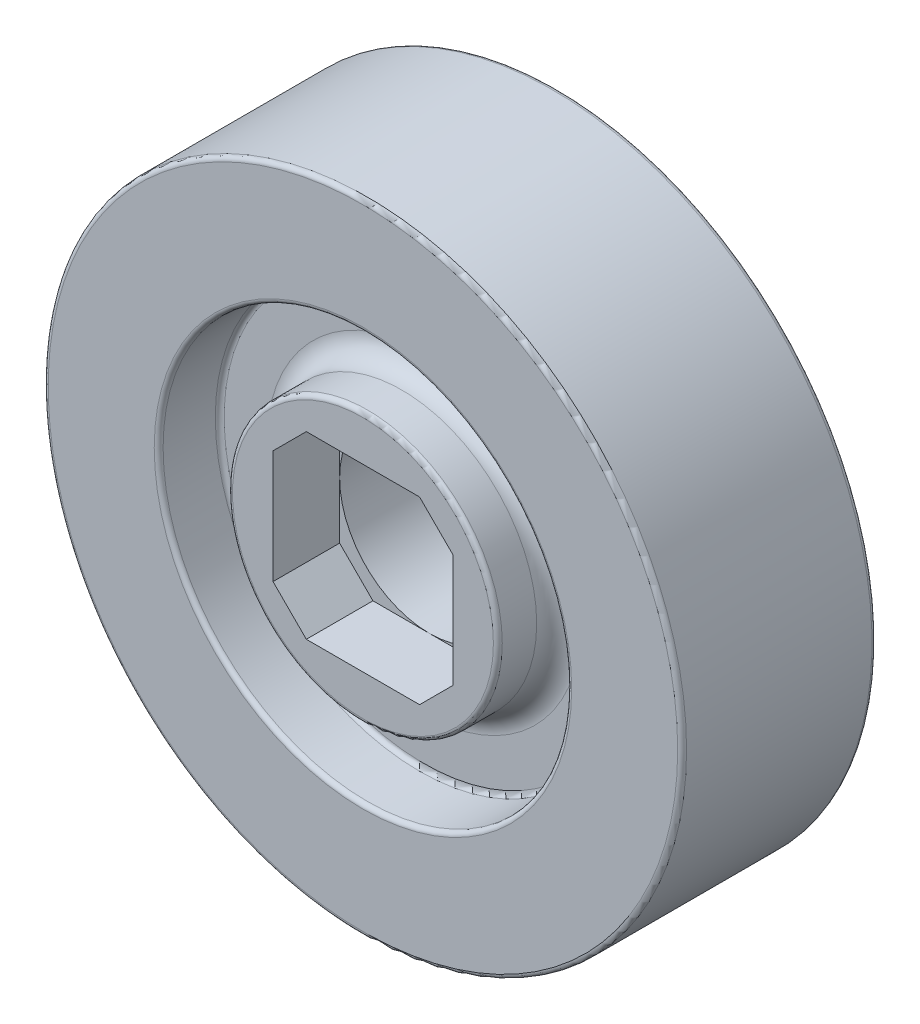
SolidWorks part; units mm, degrees
material "POLYURETHANE (11671)"
ref_plane "Front Plane" through (0, 0, 0) normal (0, 0, 1) x (1, 0, 0)
ref_plane "Top Plane" through (0, 0, 0) normal (0, 1, 0) x (1, 0, 0)
ref_plane "Right Plane" through (0, 0, 0) normal (1, 0, 0) x (0, 0, -1)
sketch "Sketch1" plane through (0, 0, 0) normal (0, 1, 0) x (1, 0, 0)
  line L0 (-36.5125, 22.225) -> (-36.5125, 0)
  line L1 (-36.5125, 0) -> (-23.368, 0)
  line L2 (-23.368, 0) -> (-23.368, 6.985)
  line L3 (-23.368, 6.985) -> (-15.4305, 6.985)
  line L4 (-15.4305, 6.985) -> (-15.4305, 0)
  line L5 (-15.4305, 0) -> (-10.287, 0)
  line L6 (-10.287, 0) -> (-10.287, 18.288)
  line L7 (-10.287, 18.288) -> (-15.494, 18.288)
  line L8 (-15.494, 18.288) -> (-15.494, 15.24)
  line L9 (-15.494, 15.24) -> (-23.368, 15.24)
  line L10 (-23.368, 15.24) -> (-23.368, 22.225)
  line L11 (-23.368, 22.225) -> (-36.5125, 22.225)
  dimension "D1" = 22.225
  dimension "D2" = 6.985
  dimension "D3" = 36.5125
  dimension "D4" = 23.368
  dimension "D5" = 15.4305
  dimension "D6" = 10.287
  dimension "D7" = 6.985
  dimension "D8" = 3.048
  dimension "D9" = 15.494
ref_axis "Axis1" through (0, 0, -23.3362) along (0, 0, 1)
revolve "Revolve1" add sketch "Sketch1" angle 360 about axis through (0, 0, -23.3362) along (0, 0, 1)
sketch "Sketch2" plane through (0, 0, 0) normal (0, 0, 1) x (1, 0, 0)
  line L1 (-10.287, -10.287) -> (10.287, -10.287)
  line L2 (-10.287, -10.287) -> (-10.287, 10.287)
  line L3 (-10.287, 10.287) -> (10.287, 10.287)
  line L4 (10.287, -10.287) -> (10.287, 10.287)
  line L5 (-10.287, -10.287) -> (10.287, 10.287) construction
  line L6 (-10.287, 10.287) -> (10.287, -10.287) construction
  point P0 (0, 0)
  dimension "D1" = 20.574
extrude "Cut-Extrude1" cut sketch "Sketch2" against normal blind 7.62
chamfer "Chamfer1" distance 3.81 angle 45 4 edges at (-10.287, -10.287, -3.81) (10.287, -10.287, -3.81) (10.287, 10.287, -3.81) (-10.287, 10.287, -3.81)
fillet "Fillet1" radius 2.54 3 edges at (-15.4305, 0, -6.985) (-15.494, 0, -18.288) (-23.368, 0, -15.24)
fillet "Fillet2" radius 0.508 6 edges at (-36.5125, 0, 0) (-36.5125, 0, -22.225) (-23.368, 0, -22.225) (-15.4305, 0, 0) (-23.368, 0, -6.985) (-23.368, 0, 0)
